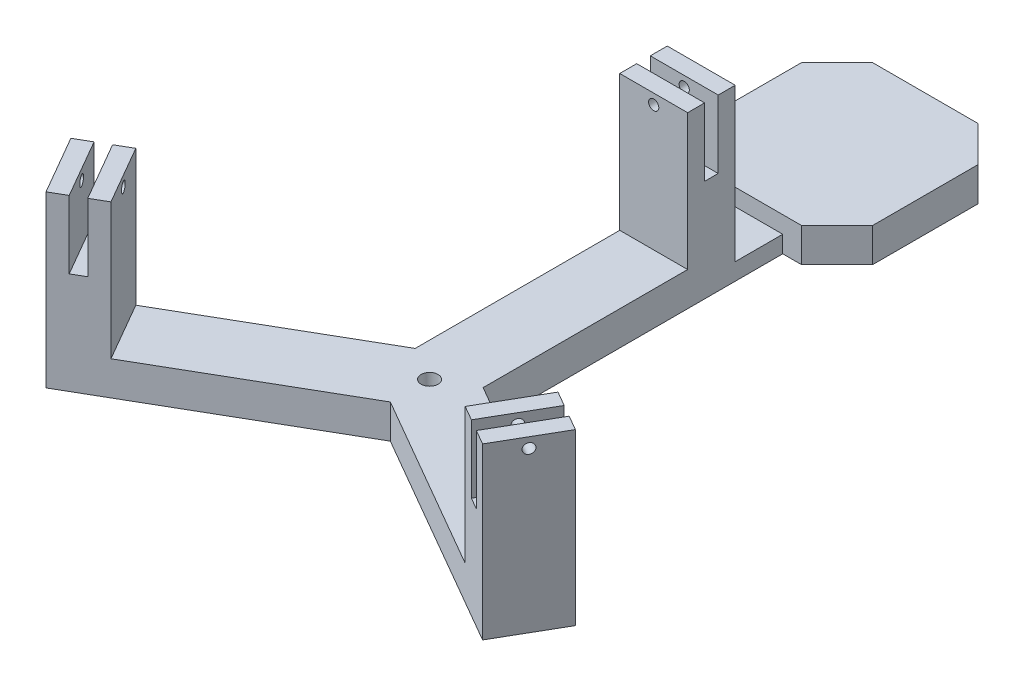
SolidWorks part; units mm, degrees
ref_plane "Front Plane" through (0, 0, 0) normal (0, 0, 1) x (1, 0, 0)
ref_plane "Top Plane" through (0, 0, 0) normal (0, 1, 0) x (1, 0, 0)
ref_plane "Right Plane" through (0, 0, 0) normal (1, 0, 0) x (0, 0, -1)
sketch "Sketch1" plane through (0, 0, 0) normal (0, 1, 0) x (1, 0, 0)
  line L0 (0, 0) -> (-10, 5.7735)
  line L1 (-10, 5.7735) -> (-10, 80)
  line L2 (-10, 80) -> (10, 80)
  line L3 (10, 80) -> (10, 5.7735)
  line L4 (10, 5.7735) -> (0, 0)
  point P4 (0, 0)
  dimension "D1" = 120
  dimension "D2" = 20
  dimension "D3" = 80
extrude "Boss-Extrude1" add sketch "Sketch1" along normal blind 10
sketch "Sketch2" plane through (0, 10, 0) normal (0, 1, 0) x (1, 0, 0)
  line L0 (10, 5.7735) -> (10, 80) construction
  line L1 (-10, 80) -> (10, 80)
  line L2 (-10, 80) -> (-10, 66)
  line L3 (-10, 66) -> (10, 66)
  line L4 (10, 80) -> (10, 66)
  dimension "D1" = 14
extrude "Boss-Extrude2" add sketch "Sketch2" along normal blind 20
sketch "Sketch3" plane through (0, 30, 0) normal (0, 1, 0) x (1, 0, 0)
  line L0 (10, 66) -> (10, 80) construction
  line L1 (-10, 80) -> (10, 80)
  line L2 (-10, 80) -> (-10, 75)
  line L3 (-10, 75) -> (10, 75)
  line L4 (10, 80) -> (10, 75)
  line L6 (-10, 66) -> (10, 66)
  line L7 (-10, 66) -> (-10, 71)
  line L8 (-10, 71) -> (10, 71)
  line L9 (10, 66) -> (10, 71)
  dimension "D1" = 5
  dimension "D2" = 5
extrude "Boss-Extrude3" add sketch "Sketch3" along normal blind 20
sketch "Sketch4" plane through (0, 0, -66) normal (0, 0, 1) x (1, 0, 0)
  line L0 (-10, 50) -> (-10, 10) construction
  line L1 (-10, 50) -> (10, 50) construction
  circle A0 centre (0, 47) radius 1.5
  dimension "D3" = 3
  dimension "D1" = 10
  dimension "D2" = 3
extrude "Cut-Extrude1" cut sketch "Sketch4" against normal through all both and the other way through all
pattern_circular "CirPattern1" count 3 over 360 about axis through (0, 0, 0) along (0, 1, 0) of "Boss-Extrude2", "Cut-Extrude1", "Boss-Extrude1", "Boss-Extrude3"
sketch "Sketch5" plane through (0, 10, 0) normal (0, 1, 0) x (1, 0, 0)
  circle A0 centre (0, 0) radius 2.5
  dimension "D1" = 5
extrude "Cut-Extrude2" cut sketch "Sketch5" against normal through all
sketch "Sketch6" plane through (0, 0, 0) normal (0, -1, 0) x (1, 0, 0)
  circle A0 centre (0, 0) radius 2.5 construction
  dimension "D1" = 5
sketch "Sketch8" plane through (0, 0, 0) normal (0, 1, 0) x (1, 0, 0)
  line L10 (-10, 80) -> (10, 80)
  line L11 (-10, 80) -> (-10, 94)
  line L12 (-10, 94) -> (10, 94)
  line L13 (10, 80) -> (10, 94)
  point P1 (0, 0)
  point P17 (-26, 104.5)
  point P24 (0, 0)
  point P25 (-26, 135.5)
  point P26 (-15.5, 146)
  point P27 (0, 0)
  point P28 (0, 0)
  point P29 (0, 0)
  point P30 (0, 0)
  point P31 (0, 0)
  dimension "D2" = 14
  dimension "D13" = 20
sketch "Sketch11" plane through (0, 0, 0) normal (0, 1, 0) x (1, 0, 0)
  line L9 (-15.5, 94) -> (15.5, 94)
  line L14 (15.5, 94) -> (26, 104.5)
  line L15 (26, 104.5) -> (26, 135.5)
  line L16 (26, 135.5) -> (15.5, 146)
  line L17 (15.5, 146) -> (-15.5, 146)
  line L18 (-15.5, 146) -> (-26, 135.5)
  line L19 (-26, 135.5) -> (-26, 104.5)
  line L20 (-26, 104.5) -> (-15.5, 94)
  point P0 (0, 0)
  dimension "D2" = 31
  dimension "D3" = 52
  dimension "D4" = 52
  dimension "D5" = 31
  dimension "D6" = 10.5
  dimension "D7" = 10.5
  dimension "D8" = 94
  dimension "D11" = 26
extrude "Boss-Extrude7" add sketch "Sketch8" along normal blind 5
extrude "Boss-Extrude8" add sketch "Sketch11" along normal blind 10
